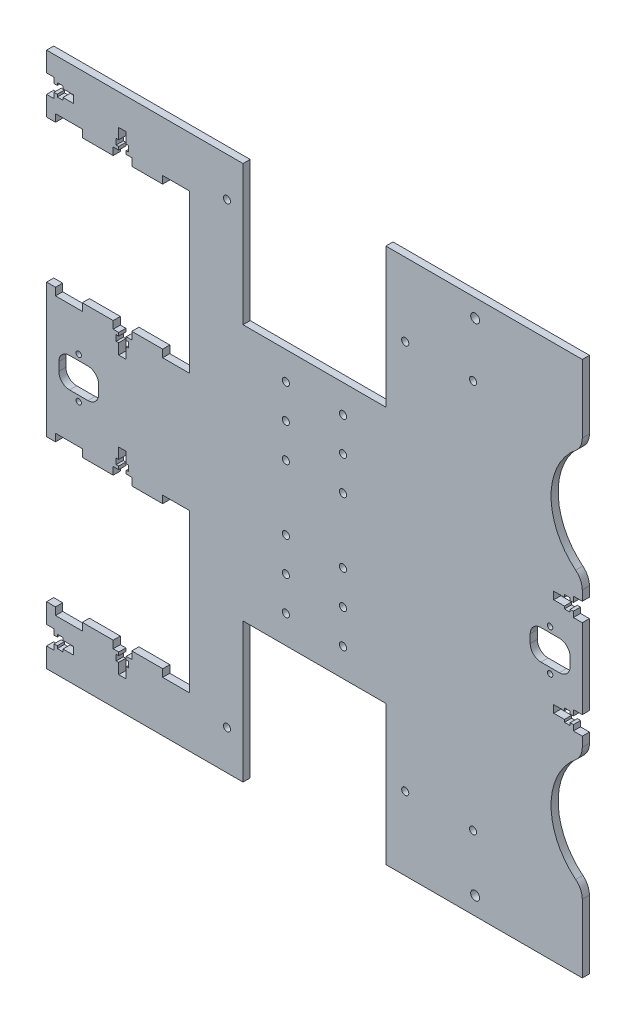
SolidWorks part; units mm, degrees
ref_plane "Plan de face" through (0, 0, 0) normal (0, 0, 1) x (1, 0, 0)
ref_plane "Plan de dessus" through (0, 0, 0) normal (0, 1, 0) x (1, 0, 0)
ref_plane "Plan de droite" through (0, 0, 0) normal (1, 0, 0) x (0, 0, -1)
sketch "Esquisse1" plane through (0, 0, 0) normal (0, 0, 1) x (1, 0, 0)
  line L1 (-150, -150) -> (150, -150)
  line L2 (-150, -150) -> (-150, 150)
  line L3 (-150, 150) -> (150, 150)
  line L4 (150, -150) -> (150, 150)
  line L5 (-150, -150) -> (150, 150) construction
  line L6 (-150, 150) -> (150, -150) construction
  point P0 (0, 0)
  dimension "D1" = 300
  dimension "D2" = 300
extrude "Boss.-Extru.1" add sketch "Esquisse1" along normal mid plane 4
sketch "Esquisse2" plane through (0, 0, 2) normal (0, 0, 1) x (1, 0, 0)
  line L0 (-150, -150) -> (150, -150) construction
  line L1 (40, -71.83) -> (-40, -71.83)
  line L2 (40, -71.83) -> (40, -150)
  line L3 (40, -150) -> (-40, -150)
  line L4 (-40, -71.83) -> (-40, -150)
  line L5 (0, 0) -> (150, 0) construction
  line L6 (150, -150) -> (150, 150) construction
  line L7 (40, -81.83) -> (40, -76.83) construction
  line L8 (-40, -76.83) -> (-40, -81.83) construction
  line L9 (40, -76.83) -> (-40, -76.83) construction
  line L10 (-40, 71.83) -> (-40, 150)
  line L11 (40, 150) -> (-40, 150)
  line L12 (40, 71.83) -> (40, 150)
  line L13 (40, 71.83) -> (-40, 71.83)
  circle A0 centre (16, -18.13) radius 2
  circle A1 centre (16, -37.13) radius 2
  circle A2 centre (16, -56.13) radius 2
  circle A3 centre (-16, -56.13) radius 2
  circle A4 centre (-16, -37.13) radius 2
  circle A5 centre (-16, -18.13) radius 2
  circle A6 centre (50.842, -109.03) radius 2
  circle A7 centre (88.842, -109.03) radius 2
  circle A8 centre (88.842, 109.03) radius 2
  circle A9 centre (50.842, 109.03) radius 2
  circle A10 centre (-16, 18.13) radius 2
  circle A11 centre (-16, 37.13) radius 2
  circle A12 centre (-16, 56.13) radius 2
  circle A13 centre (16, 56.13) radius 2
  circle A14 centre (16, 37.13) radius 2
  circle A15 centre (16, 18.13) radius 2
  dimension "D4" = 4
  dimension "D5" = 4
  dimension "D1" = 0
  dimension "D2" = 0
  dimension "D3" = 5
extrude "Enlèv. mat.-Extru.1" cut sketch "Esquisse2" against normal through all
sketch "Esquisse3" plane through (0, 0, 2) normal (0, 0, 1) x (1, 0, 0)
  line L0 (-150, 150) -> (-150, -150) construction
  line L1 (0, 0) -> (-150, 0) construction
  line L2 (40, -150) -> (150, -150) construction
  line L4 (150, -150) -> (150, 150) construction
  circle A2 centre (170, -75) radius 37.5
  circle A3 centre (170, 75) radius 37.5
  dimension "D1" = 75
  dimension "D2" = 20
  dimension "D3" = 75
extrude "Enlèv. mat.-Extru.2" cut sketch "Esquisse3" against normal through all
sketch "Esquisse4" plane through (0, 0, 2) normal (0, 0, 1) x (1, 0, 0)
  line L0 (-150, 150) -> (-150, -150) construction
  line L1 (-150, 117.5) -> (-70, 117.5)
  line L2 (-150, 117.5) -> (-150, 37.5)
  line L3 (-150, 37.5) -> (-70, 37.5)
  line L4 (-70, 117.5) -> (-70, 37.5)
  line L5 (0, 0) -> (-150, 0) construction
  line L6 (-70, 37.5) -> (-150, 117.5) construction
  line L7 (-70, 117.5) -> (-150, 37.5) construction
  line L8 (-150, -117.5) -> (-150, -37.5)
  line L9 (-150, -37.5) -> (-70, -37.5)
  line L10 (-150, -117.5) -> (-70, -117.5)
  line L11 (-70, -117.5) -> (-70, -37.5)
  dimension "D1" = 80
  dimension "D2" = 80
  dimension "D3" = 37.5
extrude "Enlèv. mat.-Extru.3" cut sketch "Esquisse4" against normal through all and the other way through all
sketch "Esquisse7" plane through (0, 0, 2) normal (0, 0, 1) x (1, 0, 0)
  line L0 (-31.6012, -128.03) -> (-49, -128.03) construction
  line L1 (-31.6012, -125.53) -> (-31.6012, -130.53) construction
  line L3 (-40, -71.83) -> (-40, -150) construction
  line L4 (0, 0) -> (150, 0) construction
  line L5 (150, -43.2786) -> (150, 43.2786) construction
  circle A0 centre (-49, -128.03) radius 2
  circle A1 centre (-49, 128.03) radius 2
  dimension "D1" = 4
  dimension "D2" = 9
extrude "Enlèv. mat.-Extru.6" cut sketch "Esquisse7" against normal through all
sketch "Esquisse8" plane through (0, 0, 2) normal (0, 0, 1) x (1, 0, 0)
  line L0 (40, -150) -> (150, -150) construction
  line L2 (0, 0) -> (150, 0) construction
  line L3 (150, -43.2786) -> (150, 43.2786) construction
  line L4 (40, -150) -> (40, -71.83) construction
  circle A0 centre (90, -140) radius 2.5
  circle A1 centre (90, 140) radius 2.5
  dimension "D1" = 5
  dimension "D2" = 10
  dimension "D3" = 50
extrude "Enlèv. mat.-Extru.7" cut sketch "Esquisse8" against normal through all
fillet "Congé1" radius 10 4 edges at (150, 106.7214, 0) (150, 43.2786, 0) (150, -43.2786, 0) (150, -106.7214, 0)
sketch "Esquisse12" plane through (0, 0, -2) normal (0, 0, -1) x (-1, 0, 0)
  line L0 (150, 133.75) -> (146, 133.75) construction
  line L1 (150, 150) -> (150, 117.5) construction
  line L2 (145.8, 128.55) -> (145.8, 138.95)
  line L3 (146, 128.75) -> (150, 128.75) construction
  line L4 (146, 128.75) -> (146, 138.75) construction
  line L5 (146, 138.75) -> (150, 138.75) construction
  line L6 (150, 128.75) -> (150, 138.75) construction
  line L7 (146, 128.75) -> (150, 138.75) construction
  line L8 (146, 138.75) -> (150, 128.75) construction
  line L9 (145.8, 138.95) -> (150.2, 138.95)
  line L10 (150.2, 128.55) -> (150.2, 138.95)
  line L11 (145.8, 128.55) -> (150.2, 128.55)
  line L12 (0, 0) -> (150, 0) construction
  line L13 (150, 37.5) -> (150, -37.5) construction
  line L14 (146, -138.75) -> (150, -128.75) construction
  line L15 (146, -128.75) -> (150, -138.75) construction
  line L16 (150, -128.75) -> (150, -138.75) construction
  line L17 (146, -138.75) -> (150, -138.75) construction
  line L18 (146, -128.75) -> (146, -138.75) construction
  line L19 (146, -128.75) -> (150, -128.75) construction
  line L20 (150, -133.75) -> (146, -133.75) construction
  line L21 (145.8, -128.55) -> (150.2, -128.55)
  line L22 (150.2, -128.55) -> (150.2, -138.95)
  line L23 (145.8, -138.95) -> (150.2, -138.95)
  line L24 (145.8, -128.55) -> (145.8, -138.95)
  point P4 (148, 133.75)
  point P24 (148, -133.75)
  dimension "D1" = 10
  dimension "D2" = 4
  dimension "D3" = 0.2
extrude "Enlèv. mat.-Extru.11" cut sketch "Esquisse12" against normal through all
sketch "Esquisse13" plane through (0, 0, -2) normal (0, 0, -1) x (-1, 0, 0)
  line L0 (145.8, 133.75) -> (134.8, 133.75) construction
  line L1 (145.8, 138.95) -> (145.8, 128.55) construction
  line L2 (134.8, 131.65) -> (134.8, 135.85)
  line L3 (134.8, 135.85) -> (140.8, 135.85)
  line L4 (140.8, 135.85) -> (140.8, 137.25)
  line L5 (140.8, 137.25) -> (144, 137.25)
  line L6 (144, 137.25) -> (144, 135.85)
  line L7 (144, 135.85) -> (145.8, 135.85)
  line L8 (145.8, 135.85) -> (145.8, 131.65)
  line L9 (144, 131.65) -> (145.8, 131.65)
  line L10 (144, 130.25) -> (144, 131.65)
  line L11 (140.8, 130.25) -> (144, 130.25)
  line L12 (140.8, 131.65) -> (140.8, 130.25)
  line L13 (134.8, 131.65) -> (140.8, 131.65)
  line L14 (0, 0) -> (-150, 0) construction
  line L15 (-150, -38.1727) -> (-150, 38.1727) construction
  line L16 (145.8, -133.75) -> (134.8, -133.75) construction
  line L17 (134.8, -131.65) -> (140.8, -131.65)
  line L18 (140.8, -131.65) -> (140.8, -130.25)
  line L19 (140.8, -130.25) -> (144, -130.25)
  line L20 (144, -130.25) -> (144, -131.65)
  line L21 (144, -131.65) -> (145.8, -131.65)
  line L22 (145.8, -135.85) -> (145.8, -131.65)
  line L23 (144, -135.85) -> (145.8, -135.85)
  line L24 (144, -137.25) -> (144, -135.85)
  line L25 (140.8, -137.25) -> (144, -137.25)
  line L26 (140.8, -135.85) -> (140.8, -137.25)
  line L27 (134.8, -135.85) -> (140.8, -135.85)
  line L28 (134.8, -131.65) -> (134.8, -135.85)
  dimension "D1" = 7
  dimension "D2" = 4.2
  dimension "D3" = 11
  dimension "D4" = 3.2
  dimension "D5" = 5
extrude "Enlèv. mat.-Extru.12" cut sketch "Esquisse13" against normal through all
sketch "Esquisse14" plane through (0, 0, -2) normal (0, 0, -1) x (-1, 0, 0)
  line L0 (-137.159, 8.366) -> (-126.839, 8.366)
  line L1 (-137.159, 7.366) -> (-126.839, 7.366) construction
  line L2 (-142.159, 2.366) -> (-142.159, -2.366) construction
  line L3 (-137.159, -7.366) -> (-126.839, -7.366) construction
  line L4 (-121.839, 2.366) -> (-121.839, -2.366) construction
  line L5 (-142.159, 7.366) -> (-121.839, -7.366) construction
  line L6 (-142.159, -7.366) -> (-121.839, 7.366) construction
  line L7 (-120.839, 2.366) -> (-120.839, -2.366)
  line L8 (-137.159, -8.366) -> (-126.839, -8.366)
  line L9 (-143.159, 2.366) -> (-143.159, -2.366)
  line L10 (0, 0) -> (0, -150) construction
  line L11 (-40, -150) -> (-150, -150) construction
  line L12 (142.159, -7.366) -> (121.839, 7.366) construction
  line L13 (142.159, 7.366) -> (121.839, -7.366) construction
  line L14 (121.839, 2.366) -> (121.839, -2.366) construction
  line L15 (137.159, -7.366) -> (126.839, -7.366) construction
  line L16 (142.159, 2.366) -> (142.159, -2.366) construction
  line L17 (137.159, 7.366) -> (126.839, 7.366) construction
  line L18 (143.159, 2.366) -> (143.159, -2.366)
  line L19 (137.159, -8.366) -> (126.839, -8.366)
  line L20 (120.839, 2.366) -> (120.839, -2.366)
  line L21 (137.159, 8.366) -> (126.839, 8.366)
  arc A0 (-139.2763, -1.1396) -> (-124.7217, -1.1396) centre (-131.999, 0) ccw construction
  arc A1 (-139.9132, 2.7397) -> (-139.9132, -2.7397) centre (-139.365, 0) ccw construction
  arc A2 (-126.839, -7.366) -> (-121.839, -2.366) centre (-126.839, -2.366) ccw construction
  arc A3 (-126.839, 7.366) -> (-121.839, 2.366) centre (-126.839, 2.366) cw construction
  arc A4 (-137.159, 7.366) -> (-142.159, 2.366) centre (-137.159, 2.366) ccw construction
  arc A5 (-142.159, -2.366) -> (-137.159, -7.366) centre (-137.159, -2.366) ccw construction
  arc A6 (-126.839, 8.366) -> (-120.839, 2.366) centre (-126.839, 2.366) cw
  arc A7 (-126.839, -8.366) -> (-120.839, -2.366) centre (-126.839, -2.366) ccw
  arc A8 (-143.159, -2.366) -> (-137.159, -8.366) centre (-137.159, -2.366) ccw
  arc A9 (-137.159, 8.366) -> (-143.159, 2.366) centre (-137.159, 2.366) ccw
  circle A10 centre (-132, -11.5) radius 1.5
  circle A11 centre (-132, 11.5) radius 1.5
  arc A12 (142.159, -2.366) -> (137.159, -7.366) centre (137.159, -2.366) cw construction
  arc A13 (137.159, 7.366) -> (142.159, 2.366) centre (137.159, 2.366) cw construction
  arc A14 (126.839, 7.366) -> (121.839, 2.366) centre (126.839, 2.366) ccw construction
  arc A15 (126.839, -7.366) -> (121.839, -2.366) centre (126.839, -2.366) cw construction
  circle A16 centre (132, 11.5) radius 1.5
  circle A17 centre (132, -11.5) radius 1.5
  arc A18 (137.159, 8.366) -> (143.159, 2.366) centre (137.159, 2.366) cw
  arc A19 (143.159, -2.366) -> (137.159, -8.366) centre (137.159, -2.366) cw
  arc A20 (126.839, -8.366) -> (120.839, -2.366) centre (126.839, -2.366) cw
  arc A21 (126.839, 8.366) -> (120.839, 2.366) centre (126.839, 2.366) ccw
  point P0 (-131.999, 0)
  point P9 (-131.999, -7.366)
  point P13 (-142.159, 0)
  point P70 (131.999, 0)
  dimension "D3" = 5
  dimension "D5" = 3
  dimension "D1" = 0
  dimension "D2" = 0
  dimension "D4" = 1
extrude "Enlèv. mat.-Extru.13" cut sketch "Esquisse14" against normal through all
sketch "Esquisse15" plane through (150, 0, 0) normal (1, 0, 0) x (0, 0, -1)
  line L0 (0, 0) -> (-2, 0) construction
  line L1 (-2, -38.1727) -> (-2, 38.1727) construction
  line L2 (-2, -32.5) -> (-2, -22.5) construction
  line L3 (-2, -32.5) -> (2, -32.5) construction
  line L4 (-2, -22.5) -> (2, -22.5) construction
  line L5 (2, -32.5) -> (2, -22.5) construction
  line L7 (0, -22.5) -> (-2, -22.5) construction
  line L8 (-2, -32.5) -> (0, -32.5) construction
  line L9 (2, -38.1727) -> (2, 38.1727) construction
  line L10 (-2.2, -32.7) -> (-2.2, -22.3)
  line L11 (-2.2, -22.3) -> (2.2, -22.3)
  line L12 (2.2, -32.7) -> (2.2, -22.3)
  line L13 (-2.2, -32.7) -> (2.2, -32.7)
  line L14 (2, 32.5) -> (2, 22.5) construction
  line L15 (-2, 22.5) -> (2, 22.5) construction
  line L16 (-2, 32.5) -> (2, 32.5) construction
  line L17 (-2, 32.5) -> (-2, 22.5) construction
  line L18 (-2.2, 32.7) -> (2.2, 32.7)
  line L19 (2.2, 32.7) -> (2.2, 22.3)
  line L20 (-2.2, 22.3) -> (2.2, 22.3)
  line L21 (-2.2, 32.7) -> (-2.2, 22.3)
  dimension "D1" = 0.2
  dimension "D2" = 0
extrude "Enlèv. mat.-Extru.14" cut sketch "Esquisse15" against normal blind 5
sketch "Esquisse16" plane through (0, 0, -2) normal (0, 0, -1) x (-1, 0, 0)
  line L0 (-145, -27.5) -> (-134, -27.5) construction
  line L1 (-145, -22.3) -> (-145, -32.7) construction
  line L2 (-145, -29.6) -> (-145, -25.4)
  line L3 (-145, -25.4) -> (-143.2, -25.4)
  line L4 (-143.2, -25.4) -> (-143.2, -24)
  line L5 (-143.2, -24) -> (-140, -24)
  line L6 (-140, -24) -> (-140, -25.4)
  line L7 (-140, -25.4) -> (-134, -25.4)
  line L8 (-134, -25.4) -> (-134, -29.6)
  line L9 (-140, -29.6) -> (-134, -29.6)
  line L10 (-140, -31) -> (-140, -29.6)
  line L11 (-143.2, -31) -> (-140, -31)
  line L12 (-143.2, -29.6) -> (-143.2, -31)
  line L13 (-145, -29.6) -> (-143.2, -29.6)
  line L14 (-150, 0) -> (-120.839, 0) construction
  line L15 (-150, -22.3) -> (-150, 22.3) construction
  line L16 (-120.839, -2.366) -> (-120.839, 2.366) construction
  line L17 (-145, 27.5) -> (-134, 27.5) construction
  line L18 (-145, 29.6) -> (-143.2, 29.6)
  line L19 (-143.2, 29.6) -> (-143.2, 31)
  line L20 (-143.2, 31) -> (-140, 31)
  line L21 (-140, 31) -> (-140, 29.6)
  line L22 (-140, 29.6) -> (-134, 29.6)
  line L23 (-134, 25.4) -> (-134, 29.6)
  line L24 (-140, 25.4) -> (-134, 25.4)
  line L25 (-140, 24) -> (-140, 25.4)
  line L26 (-143.2, 24) -> (-140, 24)
  line L27 (-143.2, 25.4) -> (-143.2, 24)
  line L28 (-145, 25.4) -> (-143.2, 25.4)
  line L29 (-145, 29.6) -> (-145, 25.4)
  dimension "D1" = 4.2
  dimension "D2" = 7
  dimension "D3" = 3.2
  dimension "D4" = 11
  dimension "D5" = 5
extrude "Enlèv. mat.-Extru.15" cut sketch "Esquisse16" against normal through all
sketch "Esquisse17" plane through (0, 0, -2) normal (0, 0, -1) x (-1, 0, 0)
  line L0 (70, 117.5) -> (150, 117.5) construction
  line L1 (145, 121.7) -> (130, 121.7)
  line L2 (145, 121.7) -> (145, 117.5)
  line L3 (145, 117.5) -> (130, 117.5)
  line L4 (130, 121.7) -> (130, 117.5)
  line L5 (145, 121.7) -> (130, 117.5) construction
  line L6 (145, 117.5) -> (130, 121.7) construction
  line L7 (150, 128.55) -> (150, 117.5) construction
  line L8 (102.3, 121.7) -> (112.7, 121.7)
  line L9 (102.5, 121.5) -> (112.5, 121.5) construction
  line L10 (102.5, 121.5) -> (102.5, 117.5) construction
  line L11 (102.5, 117.5) -> (112.5, 117.5) construction
  line L12 (112.5, 121.5) -> (112.5, 117.5) construction
  line L13 (102.5, 121.5) -> (112.5, 117.5) construction
  line L14 (102.5, 117.5) -> (112.5, 121.5) construction
  line L15 (112.7, 121.7) -> (112.7, 117.3)
  line L16 (102.3, 117.3) -> (112.7, 117.3)
  line L17 (102.3, 121.7) -> (102.3, 117.3)
  line L18 (107.5, 119.5) -> (107.5, 117.3) construction
  line L19 (70, 117.5) -> (85, 121.7) construction
  line L20 (70, 121.7) -> (85, 117.5) construction
  line L21 (85, 121.7) -> (85, 117.5)
  line L22 (70, 117.5) -> (85, 117.5)
  line L23 (70, 121.7) -> (70, 117.5)
  line L24 (70, 121.7) -> (85, 121.7)
  line L25 (70, 77.5) -> (150, 77.5) construction
  line L26 (70, 37.5) -> (70, 117.5) construction
  line L27 (150, 117.5) -> (150, 37.5) construction
  line L28 (0, 0) -> (150, 0) construction
  line L29 (150, 37.5) -> (150, -37.5) construction
  line L30 (70, 33.3) -> (85, 37.5) construction
  line L31 (70, 37.5) -> (85, 33.3) construction
  line L32 (107.5, 35.5) -> (107.5, 37.7) construction
  line L33 (102.5, 37.5) -> (112.5, 33.5) construction
  line L34 (102.5, 33.5) -> (112.5, 37.5) construction
  line L35 (112.5, 33.5) -> (112.5, 37.5) construction
  line L36 (102.5, 37.5) -> (112.5, 37.5) construction
  line L37 (102.5, 33.5) -> (102.5, 37.5) construction
  line L38 (102.5, 33.5) -> (112.5, 33.5) construction
  line L39 (145, 37.5) -> (130, 33.3) construction
  line L40 (145, 33.3) -> (130, 37.5) construction
  line L41 (70, 33.3) -> (85, 33.3)
  line L42 (70, 33.3) -> (70, 37.5)
  line L43 (70, 37.5) -> (85, 37.5)
  line L44 (85, 33.3) -> (85, 37.5)
  line L45 (102.3, 33.3) -> (102.3, 37.7)
  line L46 (102.3, 37.7) -> (112.7, 37.7)
  line L47 (112.7, 33.3) -> (112.7, 37.7)
  line L48 (102.3, 33.3) -> (112.7, 33.3)
  line L49 (130, 33.3) -> (130, 37.5)
  line L50 (145, 37.5) -> (130, 37.5)
  line L51 (145, 33.3) -> (145, 37.5)
  line L52 (145, 33.3) -> (130, 33.3)
  line L53 (145, -33.3) -> (130, -37.5) construction
  line L54 (145, -37.5) -> (130, -33.3) construction
  line L55 (102.5, -33.5) -> (112.5, -33.5) construction
  line L56 (102.5, -33.5) -> (102.5, -37.5) construction
  line L57 (102.5, -37.5) -> (112.5, -37.5) construction
  line L58 (112.5, -33.5) -> (112.5, -37.5) construction
  line L59 (102.5, -33.5) -> (112.5, -37.5) construction
  line L60 (102.5, -37.5) -> (112.5, -33.5) construction
  line L61 (107.5, -35.5) -> (107.5, -37.7) construction
  line L62 (70, -37.5) -> (85, -33.3) construction
  line L63 (70, -33.3) -> (85, -37.5) construction
  line L64 (70, -77.5) -> (150, -77.5) construction
  line L65 (70, -121.7) -> (85, -117.5) construction
  line L66 (70, -117.5) -> (85, -121.7) construction
  line L67 (107.5, -119.5) -> (107.5, -117.3) construction
  line L68 (102.5, -117.5) -> (112.5, -121.5) construction
  line L69 (102.5, -121.5) -> (112.5, -117.5) construction
  line L70 (112.5, -121.5) -> (112.5, -117.5) construction
  line L71 (102.5, -117.5) -> (112.5, -117.5) construction
  line L72 (102.5, -121.5) -> (102.5, -117.5) construction
  line L73 (102.5, -121.5) -> (112.5, -121.5) construction
  line L74 (145, -117.5) -> (130, -121.7) construction
  line L75 (145, -121.7) -> (130, -117.5) construction
  line L76 (145, -33.3) -> (130, -33.3)
  line L77 (145, -33.3) -> (145, -37.5)
  line L78 (145, -37.5) -> (130, -37.5)
  line L79 (130, -33.3) -> (130, -37.5)
  line L80 (102.3, -33.3) -> (112.7, -33.3)
  line L81 (112.7, -33.3) -> (112.7, -37.7)
  line L82 (102.3, -37.7) -> (112.7, -37.7)
  line L83 (102.3, -33.3) -> (102.3, -37.7)
  line L84 (85, -33.3) -> (85, -37.5)
  line L85 (70, -37.5) -> (85, -37.5)
  line L86 (70, -33.3) -> (70, -37.5)
  line L87 (70, -33.3) -> (85, -33.3)
  line L88 (70, -121.7) -> (85, -121.7)
  line L89 (70, -121.7) -> (70, -117.5)
  line L90 (70, -117.5) -> (85, -117.5)
  line L91 (85, -121.7) -> (85, -117.5)
  line L92 (102.3, -121.7) -> (102.3, -117.3)
  line L93 (102.3, -117.3) -> (112.7, -117.3)
  line L94 (112.7, -121.7) -> (112.7, -117.3)
  line L95 (102.3, -121.7) -> (112.7, -121.7)
  line L96 (130, -121.7) -> (130, -117.5)
  line L97 (145, -117.5) -> (130, -117.5)
  line L98 (145, -121.7) -> (145, -117.5)
  line L99 (145, -121.7) -> (130, -121.7)
  point P0 (137.5, 119.6)
  point P9 (107.5, 119.5)
  point P25 (77.5, 119.6)
  point P52 (77.5, 35.4)
  point P53 (137.5, 35.4)
  point P92 (137.5, -35.4)
  point P93 (77.5, -35.4)
  point P98 (77.5, -119.6)
  point P99 (137.5, -119.6)
  dimension "D1" = 5
  dimension "D2" = 4.2
  dimension "D3" = 15
  dimension "D4" = 10
  dimension "D5" = 4
  dimension "D6" = 0
  dimension "D7" = 0.2
extrude "Enlèv. mat.-Extru.16" cut sketch "Esquisse17" against normal through all
sketch "Esquisse18" plane through (0, 0, 2) normal (0, 0, 1) x (1, 0, 0)
  line L0 (-70, 77.5) -> (-150, 77.5) construction
  line L1 (-70, 121.7) -> (-70, 33.3) construction
  line L2 (-150, 117.5) -> (-150, 37.5) construction
  line L3 (-107.5, 121.7) -> (-107.5, 132.7) construction
  line L4 (-112.7, 121.7) -> (-102.3, 121.7) construction
  line L5 (-105.4, 121.7) -> (-109.6, 121.7)
  line L6 (-109.6, 121.7) -> (-109.6, 123.5)
  line L7 (-109.6, 123.5) -> (-111, 123.5)
  line L8 (-111, 123.5) -> (-111, 126.7)
  line L9 (-111, 126.7) -> (-109.6, 126.7)
  line L10 (-109.6, 126.7) -> (-109.6, 132.7)
  line L11 (-109.6, 132.7) -> (-105.4, 132.7)
  line L12 (-105.4, 126.7) -> (-105.4, 132.7)
  line L13 (-104, 126.7) -> (-105.4, 126.7)
  line L14 (-104, 123.5) -> (-104, 126.7)
  line L15 (-105.4, 123.5) -> (-104, 123.5)
  line L16 (-105.4, 121.7) -> (-105.4, 123.5)
  line L17 (-107.5, 33.3) -> (-107.5, 22.3) construction
  line L18 (-105.4, 33.3) -> (-105.4, 31.5)
  line L19 (-105.4, 31.5) -> (-104, 31.5)
  line L20 (-104, 31.5) -> (-104, 28.3)
  line L21 (-104, 28.3) -> (-105.4, 28.3)
  line L22 (-105.4, 28.3) -> (-105.4, 22.3)
  line L23 (-109.6, 22.3) -> (-105.4, 22.3)
  line L24 (-109.6, 28.3) -> (-109.6, 22.3)
  line L25 (-111, 28.3) -> (-109.6, 28.3)
  line L26 (-111, 31.5) -> (-111, 28.3)
  line L27 (-109.6, 31.5) -> (-111, 31.5)
  line L28 (-109.6, 33.3) -> (-109.6, 31.5)
  line L29 (-105.4, 33.3) -> (-109.6, 33.3)
  line L30 (0, 0) -> (-150, 0) construction
  line L31 (-150, 37.5) -> (-150, -37.5) construction
  line L32 (-107.5, -33.3) -> (-107.5, -22.3) construction
  line L33 (-107.5, -121.7) -> (-107.5, -132.7) construction
  line L34 (-150, -117.5) -> (-150, -37.5) construction
  line L35 (-70, -77.5) -> (-150, -77.5) construction
  line L36 (-105.4, -33.3) -> (-109.6, -33.3)
  line L37 (-109.6, -33.3) -> (-109.6, -31.5)
  line L38 (-109.6, -31.5) -> (-111, -31.5)
  line L39 (-111, -31.5) -> (-111, -28.3)
  line L40 (-111, -28.3) -> (-109.6, -28.3)
  line L41 (-109.6, -28.3) -> (-109.6, -22.3)
  line L42 (-109.6, -22.3) -> (-105.4, -22.3)
  line L43 (-105.4, -28.3) -> (-105.4, -22.3)
  line L44 (-104, -28.3) -> (-105.4, -28.3)
  line L45 (-104, -31.5) -> (-104, -28.3)
  line L46 (-105.4, -31.5) -> (-104, -31.5)
  line L47 (-105.4, -33.3) -> (-105.4, -31.5)
  line L48 (-105.4, -121.7) -> (-105.4, -123.5)
  line L49 (-105.4, -123.5) -> (-104, -123.5)
  line L50 (-104, -123.5) -> (-104, -126.7)
  line L51 (-104, -126.7) -> (-105.4, -126.7)
  line L52 (-105.4, -126.7) -> (-105.4, -132.7)
  line L53 (-109.6, -132.7) -> (-105.4, -132.7)
  line L54 (-109.6, -126.7) -> (-109.6, -132.7)
  line L55 (-111, -126.7) -> (-109.6, -126.7)
  line L56 (-111, -123.5) -> (-111, -126.7)
  line L57 (-109.6, -123.5) -> (-111, -123.5)
  line L58 (-109.6, -121.7) -> (-109.6, -123.5)
  line L59 (-105.4, -121.7) -> (-109.6, -121.7)
  dimension "D1" = 7
  dimension "D2" = 4.2
  dimension "D3" = 3.2
  dimension "D4" = 11
  dimension "D5" = 5
extrude "Enlèv. mat.-Extru.17" cut sketch "Esquisse18" against normal through all
